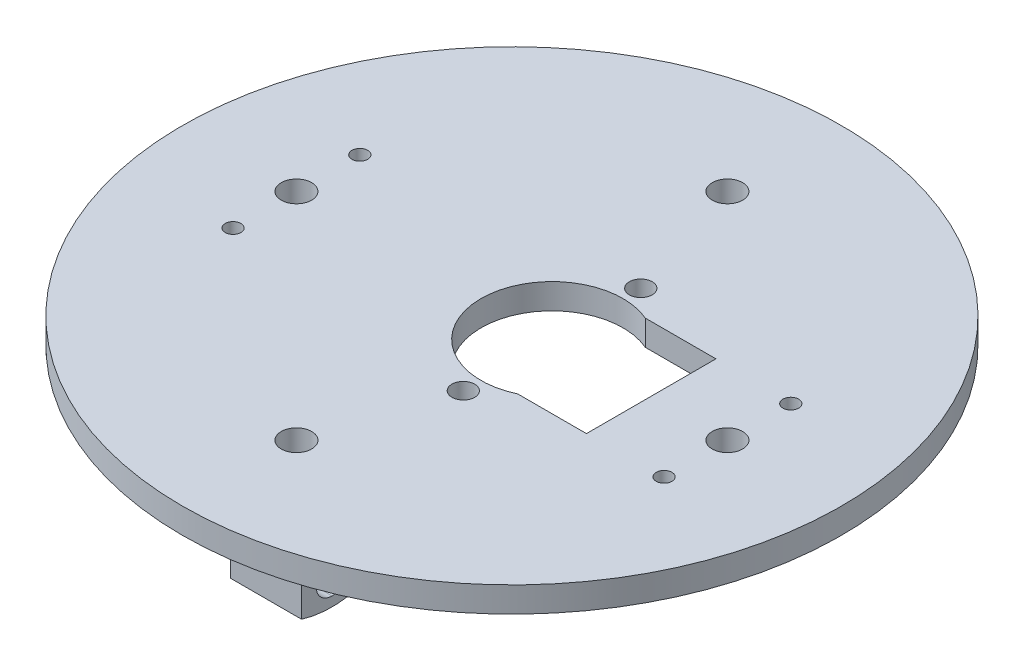
SolidWorks part; units mm, degrees
ref_plane "Front Plane" through (0, 0, 0) normal (0, 0, 1) x (1, 0, 0)
ref_plane "Top Plane" through (0, 0, 0) normal (0, 1, 0) x (1, 0, 0)
ref_plane "Right Plane" through (0, 0, 0) normal (1, 0, 0) x (0, 0, -1)
sketch "Sketch1" plane through (0, 0, 0) normal (0, 1, 0) x (1, 0, 0)
  line L0 (65, 5) -> (65, -5) construction
  line L1 (-5, 65) -> (5, 65) construction
  line L2 (-5, 65) -> (-5, 20) construction
  line L3 (-5, 20) -> (5, 20) construction
  line L4 (5, 65) -> (5, 20) construction
  line L5 (-5, 65) -> (5, 20) construction
  line L6 (-5, 20) -> (5, 65) construction
  line L7 (65, 5) -> (20, 5) construction
  line L8 (20, 5) -> (20, -5) construction
  line L9 (65, -5) -> (20, -5) construction
  line L10 (65, 5) -> (20, -5) construction
  line L11 (20, 5) -> (65, -5) construction
  line L12 (5, -65) -> (-5, -65) construction
  line L13 (5, -65) -> (5, -20) construction
  line L14 (5, -20) -> (-5, -20) construction
  line L15 (-5, -65) -> (-5, -20) construction
  line L16 (5, -65) -> (-5, -20) construction
  line L17 (5, -20) -> (-5, -65) construction
  line L18 (-65, -5) -> (-65, 5) construction
  line L19 (-65, -5) -> (-20, -5) construction
  line L20 (-20, -5) -> (-20, 5) construction
  line L21 (-65, 5) -> (-20, 5) construction
  line L22 (-65, -5) -> (-20, 5) construction
  line L23 (-20, -5) -> (-65, 5) construction
  line L24 (0, -55) -> (0, 55) construction
  circle A0 centre (0, 0) radius 65
  circle A1 centre (0, 0) radius 5
  circle A2 centre (0, 42.5) radius 3
  circle A3 centre (42.5, 0) radius 3
  circle A4 centre (0, -42.5) radius 3
  circle A5 centre (-42.5, 0) radius 3
  circle A6 centre (-42.5, -12.5) radius 1.55
  circle A7 centre (-42.5, 12.5) radius 1.55
  circle A8 centre (42.5, -12.5) radius 1.55
  circle A9 centre (42.5, 12.5) radius 1.55
  point P3 (0, 42.5)
  point P11 (42.5, 0)
  point P16 (0, -42.5)
  point P21 (-42.5, 0)
  point P26 (0, 0)
  point P36 (0, 0)
  point P38 (0, 0)
  point P39 (0, 0)
  point P46 (0, 0)
  point P47 (0, 0)
  point P48 (0, 0)
  point P49 (0, 0)
  point P50 (0, 0)
  point P51 (0, 0)
  point P52 (0, 0)
  dimension "D1" = 130
  dimension "D5" = 10
  dimension "D6" = 6
  dimension "D8" = 3.1
  dimension "D2" = 10
  dimension "D3" = 45
  dimension "D9" = 25
  dimension "D10" = 12.5
  dimension "D4" = 4
  dimension "D7" = 4
extrude "Boss-Extrude1" add sketch "Sketch1" along normal blind 5
sketch "Sketch2" plane through (0, 0, 0) normal (0, -1, 0) x (-1, 0, 0)
  circle A3 centre (-7.9995, -0.0923) radius 14
  circle A5 centre (-2.1282, -3.2886) radius 0.0329 construction
  circle A6 centre (0, 0) radius 4.5 construction
  circle A12 centre (0, 0) radius 5 construction
  dimension "D1" = 8
  dimension "D2" = 28
extrude "Cut-Extrude2" cut sketch "Sketch2" against normal blind 10
sketch "Sketch3" plane through (0, 0, 0) normal (0, -1, 0) x (-1, 0, 0)
  line L1 (-10.1618, -12.767) -> (-27.4636, -12.767)
  line L2 (-10.1618, -12.767) -> (-10.1618, 12.767)
  line L3 (-10.1618, 12.767) -> (-27.4636, 12.767)
  line L4 (-27.4636, -12.767) -> (-27.4636, 12.767)
  line L5 (-10.1618, -12.767) -> (-27.4636, 12.767) construction
  line L6 (-10.1618, 12.767) -> (-27.4636, -12.767) construction
  circle A0 centre (-7.9995, -17.5923) radius 2.25
  circle A1 centre (-7.9995, 17.4077) radius 2.25
  point P6 (-18.8127, 0)
  point P11 (-27.4356, 9.4224)
  point P12 (0, 0)
extrude "Cut-Extrude3" cut sketch "Sketch3" against normal blind 10
sketch "Sketch4" plane through (0, 5, 0) normal (0, 1, 0) x (1, 0, 0)
  line L2 (-7, 42.5) -> (-7, 22.5)
  line L3 (-7, 22.5) -> (7, 22.5)
  line L4 (7, 42.5) -> (7, 22.5)
  line L7 (-7, 42.5) -> (-7, 48.5)
  line L8 (-7, 48.5) -> (7, 48.5)
  line L9 (7, 42.5) -> (7, 48.5)
  circle A0 centre (0, 42.5) radius 3
  point P6 (0, 48.5)
  dimension "D1" = 14
  dimension "D2" = 20
  dimension "D3" = 6
extrude "Boss-Extrude2" add sketch "Sketch4" against normal blind 22.5 from surface at -5 starting at face at (7.9995, 0, 15.3423)
sketch "Sketch6" plane through (0, -22.5, 0) normal (0, -1, 0) x (-1, 0, 0)
  line L0 (-7, 22.5) -> (7, 22.5) construction
  line L1 (-3, 42.5) -> (3, 42.5)
  line L2 (-3, 42.5) -> (-3, 22.5)
  line L3 (-3, 22.5) -> (3, 22.5)
  line L4 (3, 42.5) -> (3, 22.5)
  circle A0 centre (0, 42.5) radius 3 construction
extrude "Cut-Extrude4" cut sketch "Sketch6" against normal blind 22.5
sketch "Sketch7" plane through (7, 0, 0) normal (1, 0, 0) x (0, 0, -1)
  line L5 (42.5, 0) -> (42.5, -22.5) construction
  line L6 (22.5, 0) -> (48.5, 0) construction
  line L7 (12.396, 0) -> (22.5, 0)
  line L8 (48.5, -29.5) -> (48.5, -19.0788)
  line L9 (48.5, -22.5) -> (48.5, 0) construction
  arc A7 (42.5, -18.1) -> (42.5, -11.9) centre (42.5, -15) ccw
  arc A8 (30.4153, -8.886) -> (45.5834, -14.6797) centre (42.5, 0) ccw construction
  arc A9 (34.5667, -8.8697) -> (42.5, -11.9) centre (42.5, 0) ccw
  arc A10 (30.4333, -13.4909) -> (42.5, -18.1) centre (42.5, 0) ccw
  arc A11 (34.5667, -8.8697) -> (30.4333, -13.4909) centre (32.5, -11.1803) ccw
  arc A12 (22.5, 0) -> (48.5, -19.0788) centre (42.5, 0) ccw
  arc A13 (12.396, 0) -> (48.5, -29.5) centre (42.5, 0) ccw
  dimension "D2" = 15
  dimension "D1" = 6.2
  dimension "D3" = 10
extrude "Cut-Extrude5" cut sketch "Sketch7" against normal up to surface (14 mm away) up to face at (-7, -11.25, -35.5)
mirror "Mirror1" about plane through (0, 0, 0) normal (0, 0, 1) of "Cut-Extrude4", "Cut-Extrude5", "Boss-Extrude2"
sketch "Sketch8" plane through (7, 0, 0) normal (1, 0, 0) x (0, 0, -1)
  line L0 (45.6, -15) -> (20.919, -15) construction
  arc A0 (42.5, -18.1) -> (42.5, -11.9) centre (42.5, -15) ccw construction
